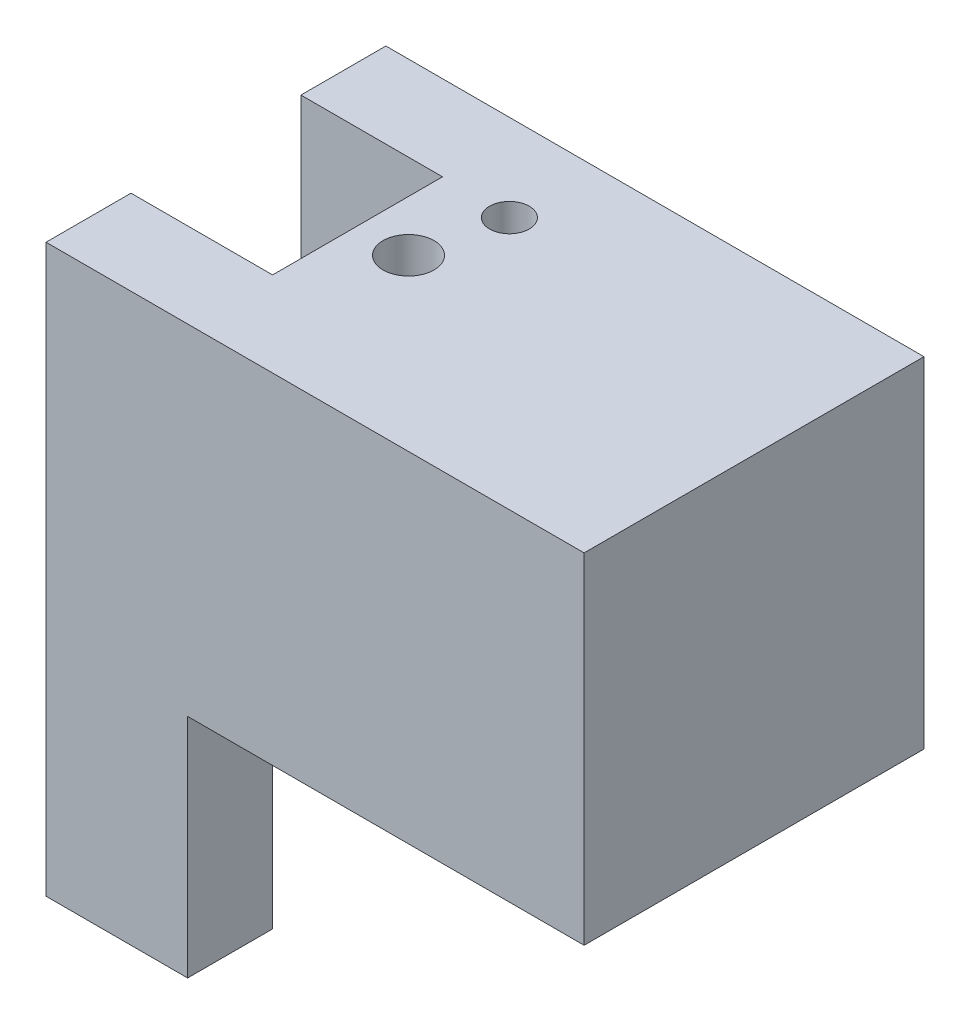
SolidWorks part; units mm, degrees
ref_plane "Plan de face" through (0, 0, 0) normal (0, 0, 1) x (1, 0, 0)
ref_plane "Plan de dessus" through (0, 0, 0) normal (0, 1, 0) x (1, 0, 0)
ref_plane "Plan de droite" through (0, 0, 0) normal (1, 0, 0) x (0, 0, -1)
sketch "Esquisse1" plane through (0, 0, 0) normal (0, 0, 1) x (1, 0, 0)
  line L1 (-73.0526, 77.3879) -> (-3.0526, 77.3879)
  line L2 (-73.0526, 77.3879) -> (-73.0526, 17.3879)
  line L3 (-73.0526, 17.3879) -> (-3.0526, 17.3879)
  line L4 (-3.0526, 77.3879) -> (-3.0526, 17.3879)
  dimension "D1" = 70
  dimension "D2" = 60
extrude "Boss.-Extru.1" add sketch "Esquisse1" along normal blind 60
sketch "Esquisse2" plane through (-73.0526, 0, 0) normal (-1, 0, 0) x (0, 0, 1)
  line L0 (60, 17.3879) -> (0, 17.3879) construction
  line L1 (0, 77.3879) -> (15, 77.3879)
  line L2 (0, 77.3879) -> (0, 17.3879)
  line L3 (0, 17.3879) -> (15, 17.3879)
  line L4 (15, 77.3879) -> (15, 17.3879)
  line L6 (60, 77.3879) -> (45, 77.3879)
  line L7 (60, 77.3879) -> (60, 17.3879)
  line L8 (60, 17.3879) -> (45, 17.3879)
  line L9 (45, 77.3879) -> (45, 17.3879)
  dimension "D1" = 15
  dimension "D2" = 15
extrude "Boss.-Extru.2" add sketch "Esquisse2" along normal blind 25
sketch "Esquisse3" plane through (0, 17.3879, 0) normal (0, -1, 0) x (1, 0, 0)
  line L0 (-98.0526, 0) -> (-3.0526, 0) construction
  line L1 (-98.0526, 60) -> (-73.0526, 60)
  line L2 (-98.0526, 60) -> (-98.0526, 45)
  line L3 (-98.0526, 45) -> (-73.0526, 45)
  line L4 (-73.0526, 60) -> (-73.0526, 45)
  line L5 (-98.0526, 15) -> (-73.0526, 15)
  line L6 (-98.0526, 15) -> (-98.0526, 0)
  line L7 (-98.0526, 0) -> (-73.0526, 0)
  line L8 (-73.0526, 15) -> (-73.0526, 0)
extrude "Boss.-Extru.3" add sketch "Esquisse3" along normal blind 40
sketch "Esquisse4" plane through (0, 17.3879, 0) normal (0, -1, 0) x (1, 0, 0)
  line L0 (-73.0526, 45) -> (-73.0526, 15) construction
  circle A0 centre (-64.0526, 30) radius 4.5
  point P0 (-64.0526, 30)
  point P1 (-73.0526, 30)
  dimension "D2" = 9
  dimension "D1" = 9
hole_wizard "Trou taraudé M8x1.01" positions "Esquisse3D3" profile "Esquisse9" tap size "M8x1.0" standard "Ansi Métrique"
sketch3d "Esquisse3D3"
  point P0 (-60.9092, 77.3879, 15.3345)
sketch "Esquisse9" plane through (-60.9092, 77.3879, 15.3345) normal (1, 0, 0) x (0, 0, 1)
  line L0 (0, 0) -> (0, 23.103)
  line L1 (0, 23.103) -> (3.5, 21)
  line L2 (3.5, 21) -> (3.5, 0)
  line L5 (3.5, 0) -> (0, 0)
  line L10 (0, 23.103) -> (-3.5, 21) construction
  line L11 (0, -6.35) -> (0, 107.95) construction
  dimension "Diamètre du trou pour taraudage" = 7
  dimension "Profondeur du trou pour taraudage" = 21
  dimension "Angle de pointe" = 118
cosmetic thread "Filetage de perçage6" parameters "D1"=16, "D2"=8
hole_wizard "Trou taraudé M10x1.02" positions "Esquisse3D5" profile "Esquisse11" tap size "M10x1.0" standard "Ansi Métrique"
sketch3d "Esquisse3D5"
  point P0 (-64.0526, 17.3879, 30)
sketch "Esquisse11" plane through (-64.0526, 17.3879, 30) normal (1, 0, 0) x (0, 0, -1)
  line L0 (0, 0) -> (0, 27.7039)
  line L1 (0, 27.7039) -> (4.5, 25)
  line L2 (4.5, 25) -> (4.5, 0)
  line L5 (4.5, 0) -> (0, 0)
  line L10 (0, 27.7039) -> (-4.5, 25) construction
  line L11 (0, -6.35) -> (0, 107.95) construction
  dimension "Diamètre du trou pour taraudage" = 9
  dimension "Profondeur du trou pour taraudage" = 25
  dimension "Angle de pointe" = 118
cosmetic thread "Filetage de perçage7" parameters "D1"=20, "D2"=10
extrude "Enlèv. mat.-Extru.3" cut sketch "Esquisse4" against normal up to next
